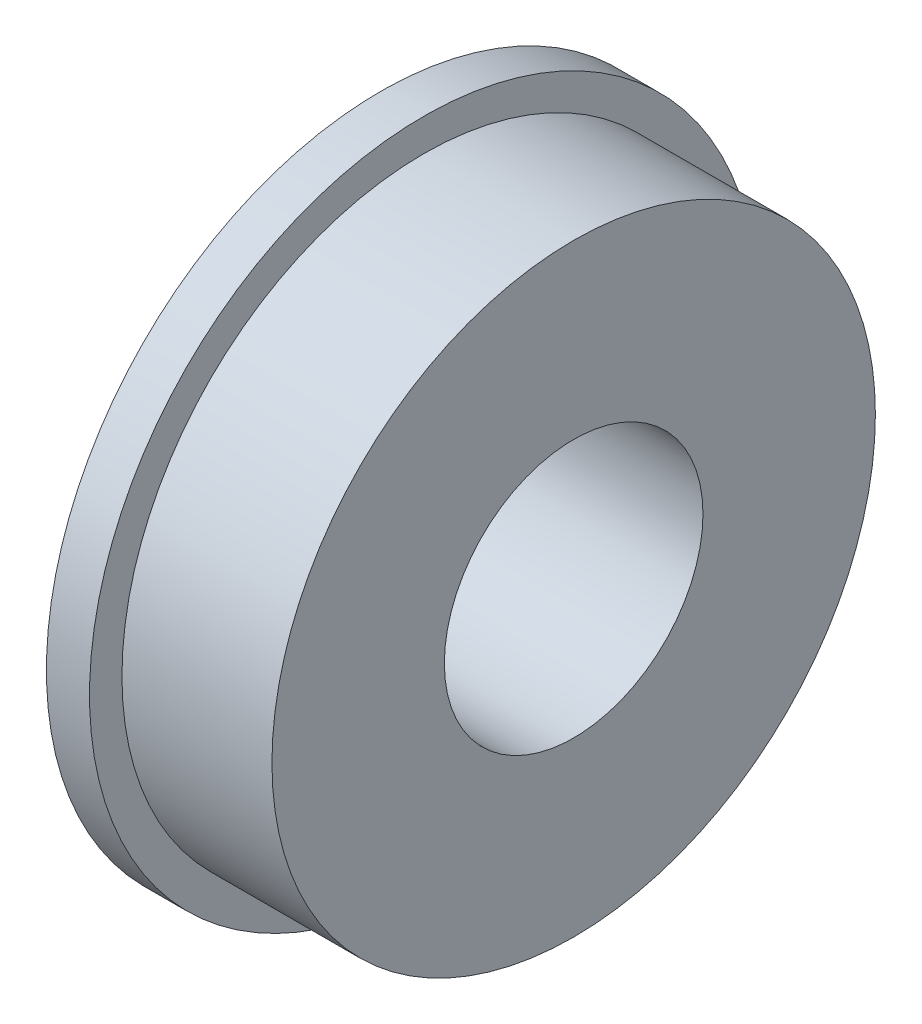
SolidWorks part; units mm, degrees
ref_plane "Front Plane" through (0, 0, 0) normal (0, 0, 1) x (1, 0, 0)
ref_plane "Top Plane" through (0, 0, 0) normal (0, 1, 0) x (1, 0, 0)
ref_plane "Right Plane" through (0, 0, 0) normal (1, 0, 0) x (0, 0, -1)
ref_plane "Plane1" through (0, 0, 0) normal (0, 0, -1) x (-1, 0, 0)
sketch "Sketch1" plane through (0, 0, 0) normal (0, 0, -1) x (-1, 0, 0)
  line L0 (-0.381, 6.35) -> (-0.381, 9.906)
  line L1 (-0.381, 9.906) -> (0, 9.906)
  line L2 (0, 9.906) -> (0, 12.3063)
  line L3 (0, 12.3063) -> (-1.5875, 12.3063)
  line L4 (-1.5875, 12.3063) -> (-1.5875, 11.1125)
  line L5 (-1.5875, 11.1125) -> (-7.112, 11.1125)
  line L6 (-7.112, 11.1125) -> (-7.112, 4.7625)
  line L7 (-7.112, 4.7625) -> (0, 4.7625)
  line L8 (0, 4.7625) -> (0, 6.35)
  line L9 (0, 6.35) -> (-0.381, 6.35)
  line L10 (-7.112, 0) -> (0, 0) construction
revolve "Revolve1" add sketch "Sketch1" angle 360 about L10
move or copy body "Body-Move/Copy1" bodies to move or copy 103
